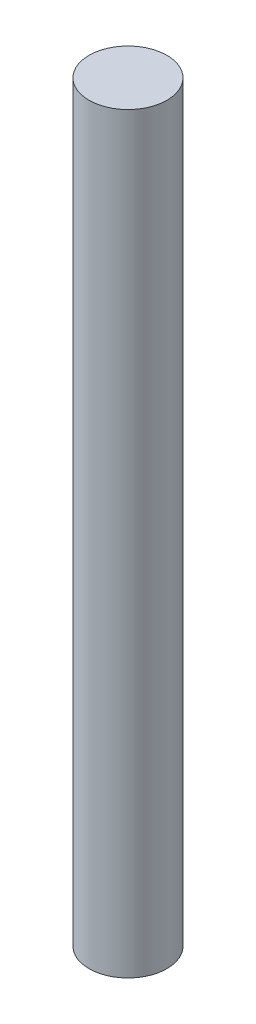
SolidWorks part; units mm, degrees
ref_plane "Front Plane" through (0, 0, 0) normal (0, 0, 1) x (1, 0, 0)
ref_plane "Top Plane" through (0, 0, 0) normal (0, 1, 0) x (1, 0, 0)
ref_plane "Right Plane" through (0, 0, 0) normal (1, 0, 0) x (0, 0, -1)
sketch "Sketch1" plane through (0, 0, 0) normal (0, 1, 0) x (1, 0, 0)
  circle A0 centre (0, 0) radius 0.95
  dimension "D1" = 1.9
extrude "Boss-Extrude1" add sketch "Sketch1" along normal blind 18.35
